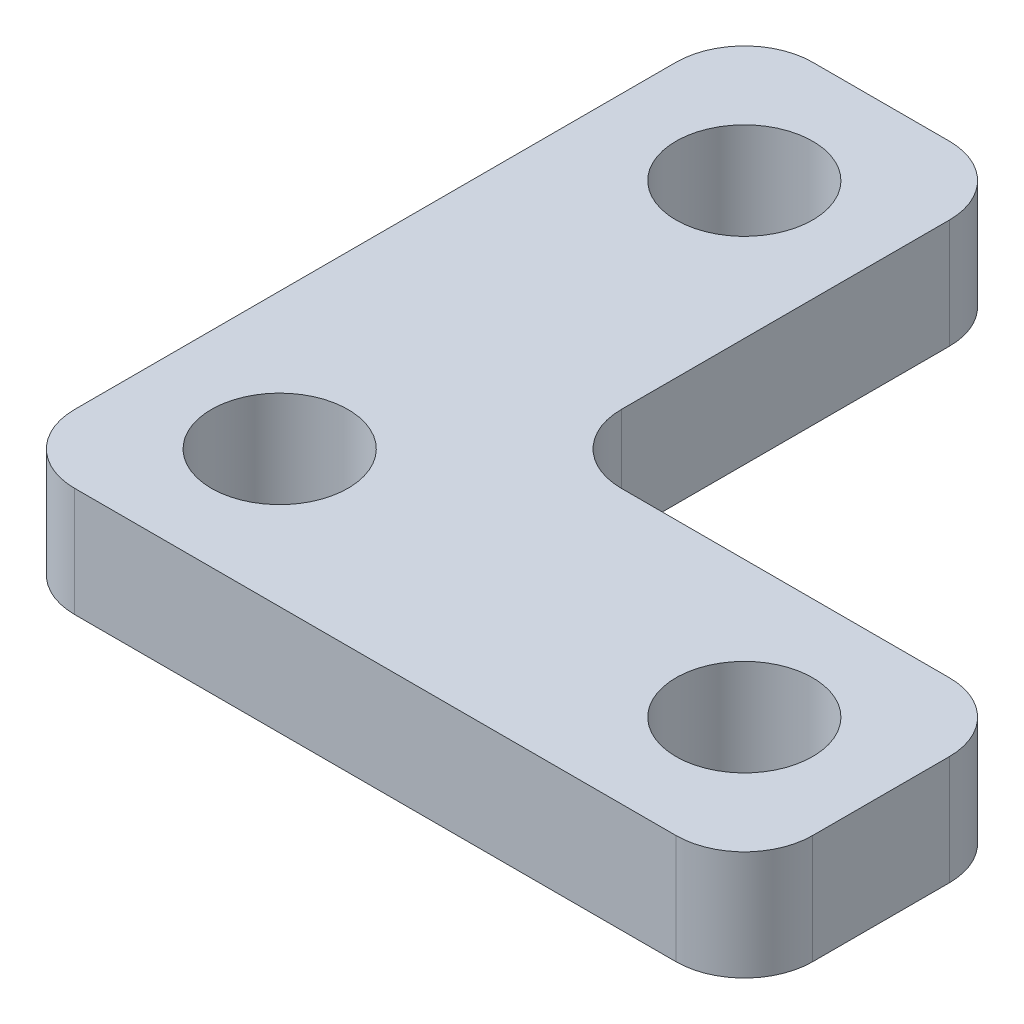
SolidWorks part; units mm, degrees
ref_plane "Front Plane" through (0, 0, 0) normal (0, 0, 1) x (1, 0, 0)
ref_plane "Top Plane" through (0, 0, 0) normal (0, 1, 0) x (1, 0, 0)
ref_plane "Right Plane" through (0, 0, 0) normal (1, 0, 0) x (0, 0, -1)
sketch "Sketch1" plane through (0, 0, 0) normal (0, 1, 0) x (1, 0, 0)
  line L0 (0, 2.5) -> (0, 24.5)
  line L1 (2.5, 27) -> (7.5, 27)
  line L2 (10, 24.5) -> (10, 12.5)
  line L3 (12.5, 10) -> (24.5, 10)
  line L4 (27, 7.5) -> (27, 2.5)
  line L5 (24.5, 0) -> (2.5, 0)
  circle A0 centre (22, 5) radius 2.5
  circle A1 centre (5, 5) radius 2.5
  circle A2 centre (5, 22) radius 2.5
  arc A3 (10, 12.5) -> (12.5, 10) centre (12.5, 12.5) ccw
  arc A4 (7.5, 27) -> (10, 24.5) centre (7.5, 24.5) cw
  arc A5 (0, 24.5) -> (2.5, 27) centre (2.5, 24.5) cw
  arc A6 (0, 2.5) -> (2.5, 0) centre (2.5, 2.5) ccw
  arc A7 (24.5, 0) -> (27, 2.5) centre (24.5, 2.5) ccw
  arc A8 (27, 7.5) -> (24.5, 10) centre (24.5, 7.5) ccw
  point P13 (0, 0)
  point P14 (0, 0)
  point P15 (4.269, 19.3725)
  point P16 (17.65, 4.1259)
  point P25 (0, 0)
  dimension "D1" = 5
  dimension "D10" = 2.5
  dimension "D2" = 17
  dimension "D3" = 17
  dimension "D4" = 5
  dimension "D5" = 5
  dimension "D6" = 5
  dimension "D7" = 5
  dimension "D8" = 5
  dimension "D9" = 5
extrude "Boss-Extrude1" add sketch "Sketch1" along normal blind 4
